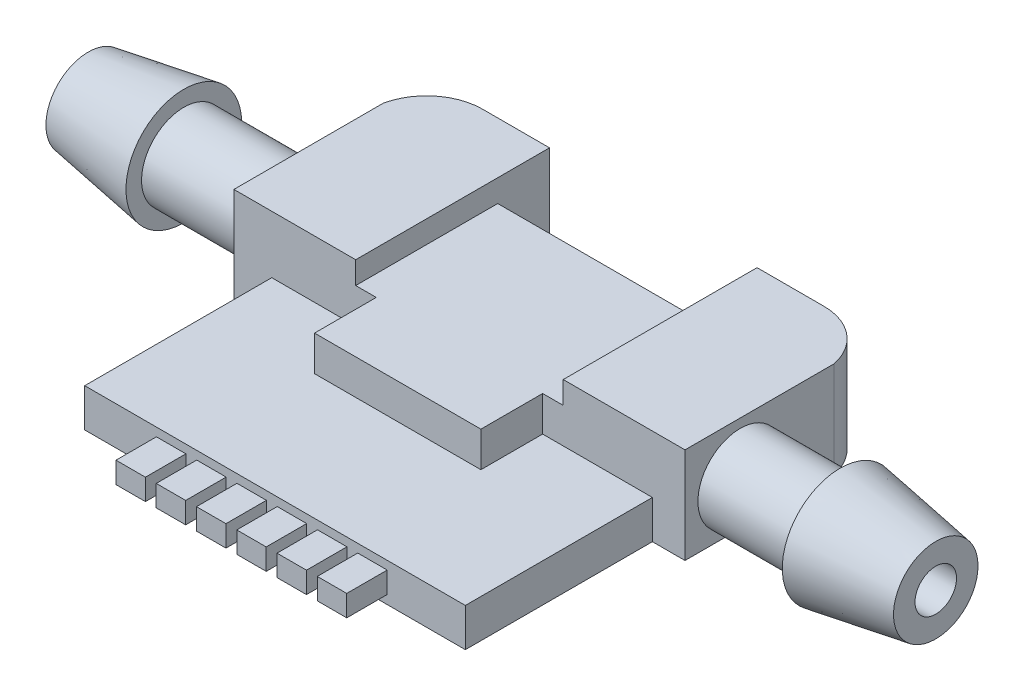
SolidWorks part; units mm, degrees
ref_plane "前视基准面" through (0, 0, 0) normal (0, 0, 1) x (1, 0, 0)
ref_plane "上视基准面" through (0, 0, 0) normal (0, 1, 0) x (1, 0, 0)
ref_plane "右视基准面" through (0, 0, 0) normal (1, 0, 0) x (0, 0, -1)
sketch "草图2" plane through (0, 0, 0) normal (0, 1, 0) x (1, 0, 0)
  line L0 (-91.8671, 33.212) -> (142.7996, 33.212) construction
  line L1 (51.6667, 97.5) -> (258.3333, 97.5) construction
  line L3 (38.6988, 9.4728) -> (14.8766, 9.4728)
  line L4 (38.6988, 9.4728) -> (38.6988, 30.0691)
  line L5 (38.6988, 30.0691) -> (14.8766, 30.0691)
  line L6 (14.8766, 9.4728) -> (14.8766, 30.0691)
sketch "草图4" plane through (0, 0, 0) normal (0, 1, 0) x (1, 0, 0)
  line L1 (20.1287, 33.3103) -> (20.1287, 30.0691)
  line L2 (21.4169, 17.3152) -> (31.8298, 17.3152)
  line L3 (31.8298, 17.3152) -> (31.8298, 21.1798)
  line L4 (31.8298, 21.1798) -> (40.7398, 21.1798)
  line L5 (40.7398, 21.1798) -> (40.7398, 30.5192)
  line L6 (37.3046, 33.3103) -> (33.118, 33.3103)
  line L7 (33.118, 33.3103) -> (33.118, 30.0691)
  line L8 (38.6988, 30.0691) -> (14.8766, 30.0691) construction
  line L9 (33.118, 30.0691) -> (20.1287, 30.0691)
  line L10 (15.942, 33.3103) -> (20.1287, 33.3103)
  line L11 (12.5068, 21.1798) -> (12.5068, 30.5192)
  line L12 (21.4169, 21.1798) -> (12.5068, 21.1798)
  line L13 (21.4169, 17.3152) -> (21.4169, 21.1798)
  arc A0 (15.942, 33.3103) -> (12.5068, 30.5192) centre (15.942, 29.8008) ccw
  arc A1 (37.3046, 33.3103) -> (40.7398, 30.5192) centre (37.3046, 29.8008) cw
extrude "凸台-拉伸2" add sketch "草图4" along normal blind 6
extrude "凸台-拉伸3" add sketch "草图2" along normal blind 2.4
sketch "草图6" plane through (0, 6, 0) normal (0, 1, 0) x (1, 0, 0)
  line L1 (20.1287, 30.0691) -> (33.118, 30.0691)
  line L2 (20.1287, 30.0691) -> (20.1287, 16.2637)
  line L3 (20.1287, 16.2637) -> (33.118, 16.2637)
  line L4 (33.118, 30.0691) -> (33.118, 16.2637)
extrude "切除-拉伸2" cut sketch "草图6" against normal blind 1.4
ref_plane "基准面1" through (0, 3, 0) normal (0, 1, 0) x (1, 0, 0)
sketch "草图8" plane through (0, 3, 0) normal (0, 1, 0) x (1, 0, 0)
  line L0 (6.1299, 27.0636) -> (12.3879, 27.0636)
  line L1 (12.3879, 27.0636) -> (12.3879, 24.4203)
  line L2 (12.3879, 24.4203) -> (0.1439, 24.4203)
  line L3 (0.1439, 27.0636) -> (0.1439, 24.4203)
  line L4 (26.6688, 30.1031) -> (26.6688, 17.3493) construction
  line L5 (0.1439, 27.0636) -> (6.1299, 28.0407)
  line L6 (6.1299, 28.0407) -> (6.1299, 27.0636)
  line L7 (12.3879, 24.4203) -> (0.1439, 24.4203) construction
  line L8 (40.9497, 24.4203) -> (53.1936, 24.4203) construction
  line L9 (47.2076, 28.0407) -> (47.2076, 27.0636)
  line L10 (53.1936, 27.0636) -> (47.2076, 28.0407)
  line L11 (53.1936, 27.0636) -> (53.1936, 24.4203)
  line L12 (40.9497, 24.4203) -> (53.1936, 24.4203)
  line L13 (40.9497, 27.0636) -> (40.9497, 24.4203)
  line L14 (47.2076, 27.0636) -> (40.9497, 27.0636)
  line L15 (26.7877, 30.0691) -> (26.6233, 17.3152) construction
  line L16 (38.6988, 30.0691) -> (14.8766, 30.0691) construction
  line L17 (21.4169, 17.3152) -> (31.8298, 17.3152) construction
  dimension "D1" = 53.0497
revolve "旋转5" add sketch "草图8" angle 360 about L2
sketch "草图9" plane through (0.1439, 0, 0) normal (-1, 0, 0) x (0, 0, 1)
  circle A0 centre (-24.4203, 3) radius 1.3
  circle A1 centre (-24.4203, 3) radius 2.6434 construction
  dimension "D1" = 1.3434
extrude "切除-拉伸3" cut sketch "草图9" against normal through all
sketch "草图10" plane through (0, 3, 0) normal (0, 1, 0) x (1, 0, 0)
  line L0 (21.9377, 9.4195) -> (21.9377, 6.8872)
  line L1 (19.4177, 9.4195) -> (21.2611, 9.4195)
  line L2 (19.4177, 9.4195) -> (19.4177, 6.8872)
  line L3 (19.4177, 6.8872) -> (21.2611, 6.8872)
  line L4 (21.2611, 9.4195) -> (21.2611, 6.8872)
  line L5 (21.9377, 9.4195) -> (23.7811, 9.4195)
  line L6 (23.7811, 9.4195) -> (23.7811, 6.8872)
  line L7 (21.9377, 6.8872) -> (23.7811, 6.8872)
  line L8 (24.4577, 9.4195) -> (24.4577, 6.8872)
  line L9 (24.4577, 9.4195) -> (26.3011, 9.4195)
  line L10 (26.3011, 9.4195) -> (26.3011, 6.8872)
  line L11 (24.4577, 6.8872) -> (26.3011, 6.8872)
  line L12 (26.9777, 9.4195) -> (26.9777, 6.8872)
  line L13 (26.9777, 9.4195) -> (28.8211, 9.4195)
  line L14 (28.8211, 9.4195) -> (28.8211, 6.8872)
  line L15 (26.9777, 6.8872) -> (28.8211, 6.8872)
  line L16 (29.4977, 9.4195) -> (29.4977, 6.8872)
  line L17 (29.4977, 9.4195) -> (31.3411, 9.4195)
  line L18 (31.3411, 9.4195) -> (31.3411, 6.8872)
  line L19 (29.4977, 6.8872) -> (31.3411, 6.8872)
  line L20 (32.0177, 9.4195) -> (32.0177, 6.8872)
  line L21 (32.0177, 9.4195) -> (33.8611, 9.4195)
  line L22 (33.8611, 9.4195) -> (33.8611, 6.8872)
  line L23 (32.0177, 6.8872) -> (33.8611, 6.8872)
  dimension "D1" = 6
extrude "凸台-拉伸4" add sketch "草图10" against normal blind 2.4 separate body
sketch "草图11" plane through (19.4177, 0, 0) normal (-1, 0, 0) x (0, 0, 1)
  line L0 (-9.4195, 0.6) -> (-9.4195, 3) construction
  line L1 (-6.8872, 3) -> (-9.4195, 3)
  line L2 (-6.8872, 3) -> (-6.8872, 1.9254)
  line L3 (-6.8872, 1.9254) -> (-9.4195, 1.9254)
  line L4 (-9.4195, 3) -> (-9.4195, 1.9254)
extrude "切除-拉伸4" cut sketch "草图11" against normal blind 19.4
